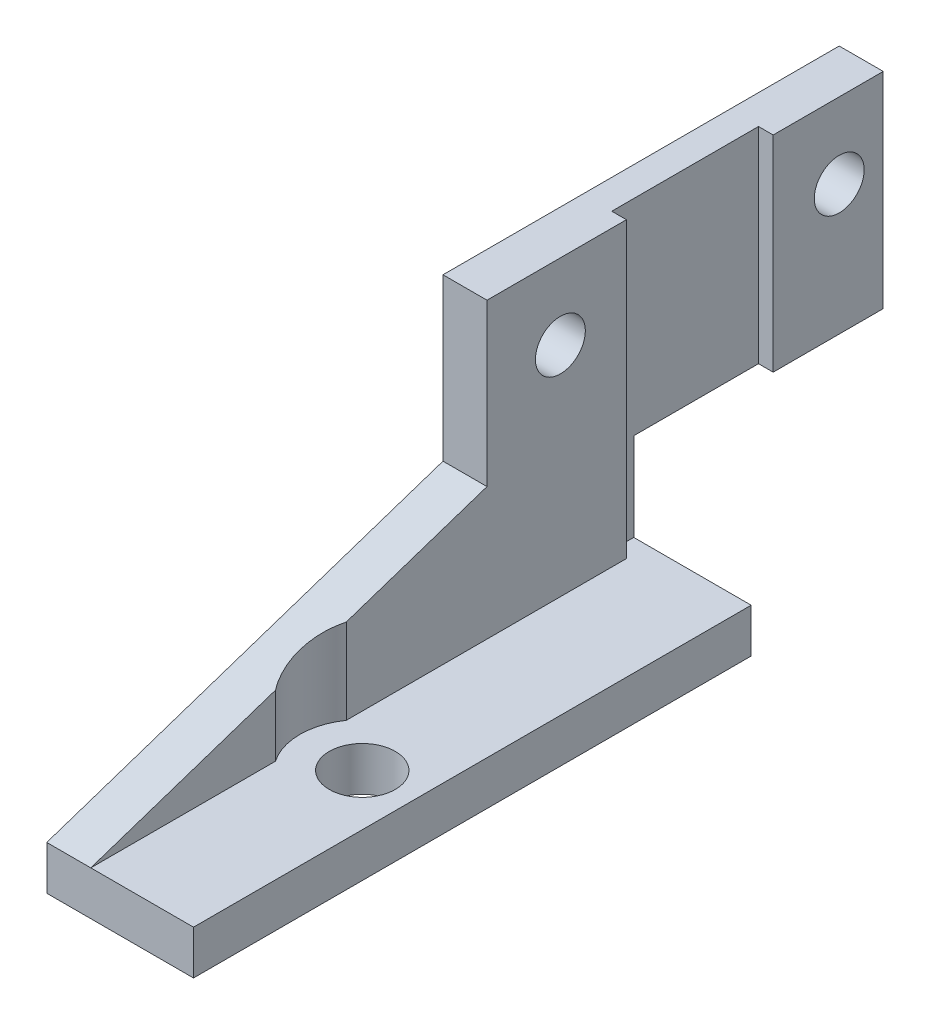
SolidWorks part; units mm, degrees
ref_plane "Front Plane" through (0, 0, 0) normal (0, 0, 1) x (1, 0, 0)
ref_plane "Top Plane" through (0, 0, 0) normal (0, 1, 0) x (1, 0, 0)
ref_plane "Right Plane" through (0, 0, 0) normal (1, 0, 0) x (0, 0, -1)
sketch "Sketch1" plane through (0, 0, 0) normal (0, 0, 1) x (1, 0, 0)
  line L0 (0, 0) -> (0, 20)
  line L1 (0, 20) -> (3, 20)
  line L2 (3, 20) -> (3, 0)
  line L3 (3, 0) -> (10, 0)
  line L4 (10, 0) -> (10, -3)
  line L5 (10, -3) -> (0, -3)
  line L8 (0, -3) -> (0, 0)
  dimension "D1" = 3
  dimension "D2" = 10
  dimension "D3" = 3
  dimension "D4" = 20
extrude "Boss-Extrude1" add sketch "Sketch1" along normal blind 27
sketch "Sketch3" plane through (3, 0, 0) normal (1, 0, 0) x (0, 0, -1)
  line L0 (-22, 14.85) -> (-3, 14.85) construction
  line L1 (-27, 20) -> (0, 20) construction
  line L2 (0, 0) -> (0, 20) construction
  circle A0 centre (-22, 14.85) radius 1.7
  circle A1 centre (-3, 14.85) radius 1.7
  dimension "D1" = 19
  dimension "D3" = 3.4
  dimension "D4" = 3.4
  dimension "D5" = 3
  dimension "D2" = 5.15
extrude "Cut-Extrude2" cut sketch "Sketch3" against normal through all
sketch "Sketch4" plane through (3, 0, 0) normal (1, 0, 0) x (0, 0, -1)
  line L0 (-27, 20) -> (0, 20) construction
  line L1 (-17.5, 20) -> (-7.5, 20)
  line L2 (-17.5, 20) -> (-17.5, 0)
  line L3 (-17.5, 0) -> (-7.5, 0)
  line L4 (-7.5, 20) -> (-7.5, 0)
  line L5 (-27, 0) -> (0, 0) construction
  circle A0 centre (-22, 14.85) radius 1.7 construction
  dimension "D1" = 10
  dimension "D2" = 4.5
extrude "Cut-Extrude3" cut sketch "Sketch4" against normal blind 1
sketch "Sketch5" plane through (0, 0, 0) normal (0, 1, 0) x (1, 0, 0)
  line L0 (10, 0) -> (3, 0) construction
  line L1 (10, -27) -> (10, 0) construction
  circle A0 centre (6.5, -9) radius 2.25
  dimension "D1" = 4.5
  dimension "D2" = 9
  dimension "D3" = 3.5
extrude "Cut-Extrude4" cut sketch "Sketch5" against normal through all
sketch "Sketch6" plane through (0, 0, 0) normal (-1, 0, 0) x (0, 0, 1)
  line L0 (27, 9) -> (54, 0)
  line L1 (27, 20) -> (27, -3) construction
  line L2 (54, 0) -> (54, -3)
  line L3 (27, -3) -> (54, -3)
  line L4 (27, 9) -> (27, -3)
  line L5 (0, 20) -> (0, -3) construction
  line L6 (27, 20) -> (0, 20) construction
  dimension "D1" = 54
  dimension "D2" = 3
  dimension "D3" = 11
extrude "Boss-Extrude2" add sketch "Sketch6" against normal up to surface (3 mm away) up to face at (3, 16.55, 22)
sketch "Sketch7" plane through (0, 0, 27) normal (0, 0, 1) x (1, 0, 0)
  line L1 (10, 0) -> (3, 0)
  line L2 (10, 0) -> (10, -3)
  line L3 (10, -3) -> (3, -3)
  line L4 (3, 0) -> (3, -3)
extrude "Boss-Extrude3" add sketch "Sketch7" along normal up to surface (27 mm away)
sketch "Sketch8" plane through (0, 0, 0) normal (0, 1, 0) x (1, 0, 0)
  line L0 (6.5, -9) -> (6.5, -39) construction
  circle A0 centre (6.5, -39) radius 2.25
  dimension "D2" = 4.5
  dimension "D1" = 30
extrude "Cut-Extrude5" cut sketch "Sketch8" against normal through all
sketch "Sketch9" plane through (0, 0, 0) normal (0, 1, 0) x (1, 0, 0)
  circle A0 centre (6.5, -39) radius 4.25
  dimension "D1" = 8.5
extrude "Cut-Extrude6" cut sketch "Sketch9" along normal through all
sketch "Sketch11" plane through (10, 0, 0) normal (1, 0, 0) x (0, 0, -1)
  line L1 (0, -3) -> (-16, -3)
  line L2 (0, -3) -> (0, 6)
  line L3 (0, 6) -> (-16, 6)
  line L4 (-16, -3) -> (-16, 6)
  dimension "D1" = 9
  dimension "D2" = 16
extrude "Cut-Extrude7" cut sketch "Sketch11" against normal through all
